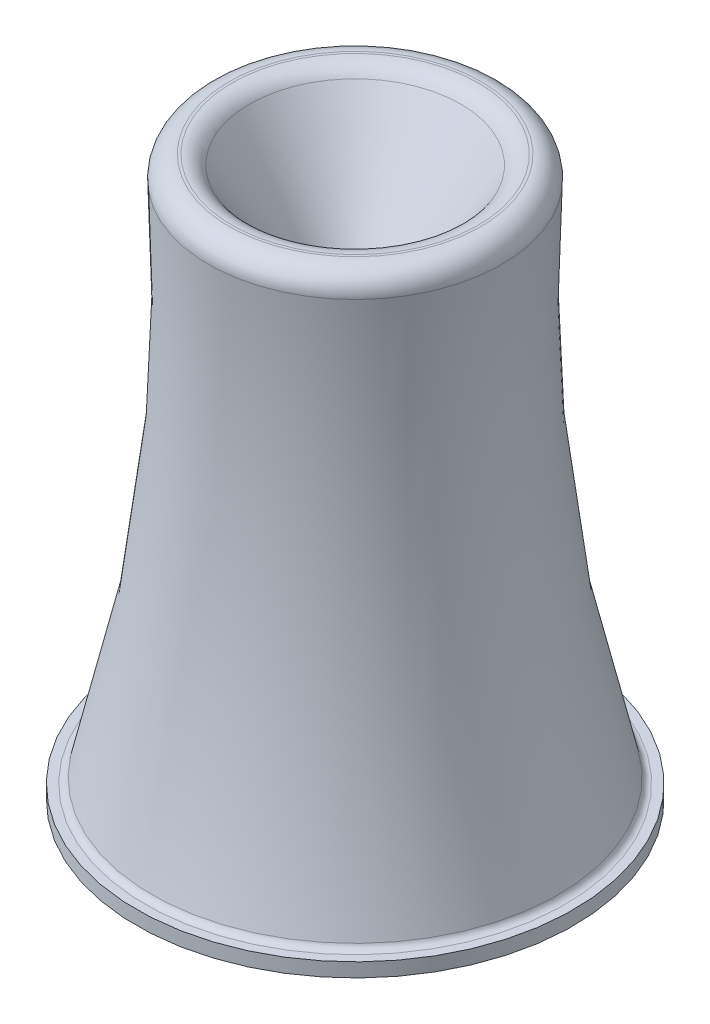
SolidWorks part; units mm, degrees
material "ABS"
ref_plane "Plan de face" through (0, 0, 0) normal (0, 0, 1) x (1, 0, 0)
ref_plane "Plan de dessus" through (0, 0, 0) normal (0, 1, 0) x (1, 0, 0)
ref_plane "Plan de droite" through (0, 0, 0) normal (1, 0, 0) x (0, 0, -1)
sketch "Esquisse1" plane through (0, 0, 0) normal (1, 0, 0) x (0, 0, -1)
  line L0 (0, 0) -> (0, 80) construction
  line L1 (31.25, 0) -> (28.2738, 0)
  line L2 (3, 60) -> (15.1127, 78.635)
  line L3 (17.6281, 80) -> (18, 80)
  line L4 (4.789, 60) -> (16.3704, 77.8175)
  line L5 (31.25, 0) -> (31.25, 2)
  line L6 (31.25, 2) -> (30.0029, 2)
  line L7 (31.25, 2) -> (29.25, 2) construction
  line L8 (17.6281, 78.5) -> (18, 78.5)
  line L10 (4.2577, 59.1825) -> (16.3704, 77.8175) construction
  line L12 (3, 60) -> (4.789, 60)
  line L13 (31.25, 0) -> (17.6987, 0) construction
  line L14 (27.8332, 1.5) -> (17.6987, 1.5) construction
  line L15 (27.8332, 1.5) -> (27.8332, 1.5) construction
  line L16 (27.8332, 1.5) -> (27.8332, 1.5) construction
  arc A0 (18, 80) -> (20.9942, 76.8141) centre (18, 77) cw
  arc A1 (15.1127, 78.635) -> (17.6281, 80) centre (17.6281, 77) cw
  arc A2 (20.9942, 76.8141) -> (29.0414, 2.7252) centre (240.5715, 63.182) ccw
  arc A3 (16.3704, 77.8175) -> (17.6281, 78.5) centre (17.6281, 77) cw
  arc A4 (18, 78.5) -> (19.4971, 76.9071) centre (18, 77) cw
  arc A5 (19.4971, 76.9071) -> (28.2738, 0) centre (240.5715, 63.182) ccw
  arc A6 (19.4971, 76.9071) -> (27.8332, 1.5) centre (240.5715, 63.182) ccw construction
  arc A7 (20.9942, 76.8141) -> (29.25, 2) centre (240.5715, 63.182) ccw construction
  arc A8 (29.0414, 2.7252) -> (30.0029, 2) centre (30.0029, 3) ccw
  point P11 (18, 80)
  point P14 (16, 80)
  point P34 (29.25, 2)
  dimension "D8" = 3
  dimension "D9" = 220
  dimension "D12" = 1
  dimension "D1" = 62.5
  dimension "D2" = 80
  dimension "D3" = 2
  dimension "D4" = 2
  dimension "D5" = 18
  dimension "D6" = 20
  dimension "D7" = 16
  dimension "D11" = 3
  dimension "D10" = 1.5
revolve "Révolution3" add sketch "Esquisse1" angle 360 about L0
